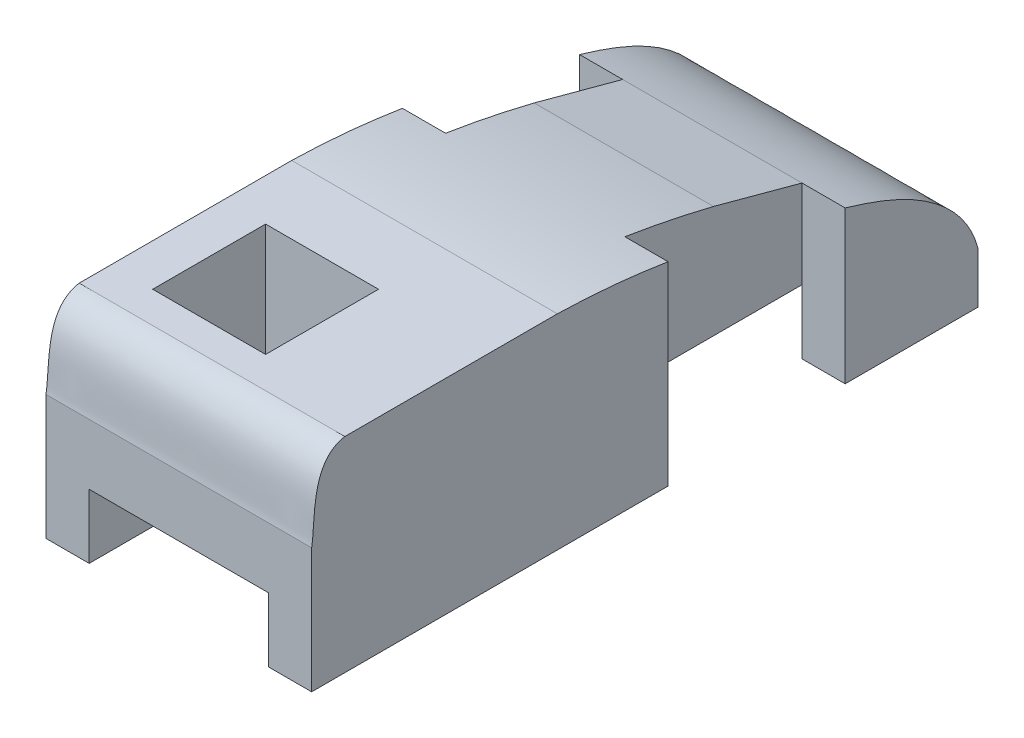
SolidWorks part; units mm, degrees
ref_plane "前视基准面" through (0, 0, 0) normal (0, 0, 1) x (1, 0, 0)
ref_plane "上视基准面" through (0, 0, 0) normal (0, 1, 0) x (1, 0, 0)
ref_plane "右视基准面" through (0, 0, 0) normal (1, 0, 0) x (0, 0, -1)
other "Configuration Table"
sketch "草图1" plane through (0, 0, 0) normal (0, 1, 0) x (1, 0, 0)
  line L1 (-50, 92.5) -> (50, 92.5)
  line L2 (-50, 92.5) -> (-50, -92.5)
  line L3 (-50, -92.5) -> (50, -92.5)
  line L4 (50, 92.5) -> (50, -92.5)
  line L5 (-50, 92.5) -> (50, -92.5) construction
  line L6 (-50, -92.5) -> (50, 92.5) construction
  point P0 (0, 0)
  dimension "D1" = 100
  dimension "D2" = 185
extrude "凸台-拉伸1" add sketch "草图1" along normal blind 100
sketch "草图2" plane through (0, 0, 92.5) normal (0, 0, 1) x (1, 0, 0)
  line L0 (-20.8417, 0) -> (-20.8417, 3.8) construction
  line L1 (-50, 0) -> (50, 0) construction
  line L2 (-20.8417, 3.8) -> (75.1632, 3.8) construction
  line L3 (75.1632, 3.8) -> (-71.0613, 3.8) construction
  line L4 (-50, 5.664) -> (-50, -9.7456) construction
  line L5 (-50, 100) -> (-50, 0) construction
  line L7 (50, 0) -> (-50, 0)
  line L8 (50, 0) -> (50, 3.8)
  line L9 (50, 3.8) -> (-50, 3.8)
  line L10 (-50, 0) -> (-50, 3.8)
  dimension "D1" = 3.8
extrude "切除-拉伸1" cut sketch "草图2" against normal offset from surface (155 mm away) 30 up to face at (0, 50, -92.5)
sketch "草图3" plane through (0, 0, 92.5) normal (0, 0, 1) x (1, 0, 0)
  line L0 (-20, 101.4471) -> (-20, -5.8655) construction
  line L1 (-4.3, 4.1859) -> (4.3, 4.1859) construction
  line L2 (-50, 3.8) -> (-20, 3.8) construction
  line L3 (-50, 3.8) -> (50, 3.8) construction
  line L4 (50, 3.8) -> (20, 3.8) construction
  line L5 (50, 3.8) -> (-50, 3.8) construction
  line L6 (20, 3.8) -> (20, 102.7774) construction
  line L7 (0, 0) -> (0, 12.6714) construction
  line L8 (-3.51, 3.8) -> (3.51, 3.8)
  line L9 (0, 3.8) -> (7.456, 3.8) construction
  line L10 (-9.3719, 10.6927) -> (9.3719, 10.6927) construction
  line L11 (-4.5, 11.5021) -> (4.5, 11.5021) construction
  line L12 (-9.3719, 10.6927) -> (-9.3719, 3.8) construction
  line L13 (-9.3719, 10.6927) -> (-4.3, 4.1859)
  line L14 (-4.3, 4.1859) -> (-4.3, 3.8) construction
  line L15 (8.9765, 11.5021) -> (8.9765, 10.6927) construction
  line L16 (9.3719, 10.6927) -> (4.3, 4.1859)
  line L17 (-4.5, 11.5021) -> (-8.9765, 11.5021)
  line L18 (4.5, 11.5021) -> (8.9765, 11.5021)
  line L19 (-8.9765, 11.5021) -> (-8.9765, 10.6927) construction
  line L21 (-4.5, 16.0021) -> (4.5, 16.0021) construction
  line L24 (-50, 100) -> (-50, 3.8) construction
  line L25 (-50, 16.0021) -> (-50, 3.8)
  line L26 (-50, 3.8) -> (-3.51, 3.8)
  line L28 (50, 100) -> (50, 3.8) construction
  line L29 (50, 16.0021) -> (50, 3.8)
  line L30 (50, 3.8) -> (3.51, 3.8)
  line L33 (20.5, 3.8) -> (3.51, 3.8)
  line L36 (-20.5, 3.8) -> (-3.51, 3.8)
  line L37 (0, 16.0021) -> (4, 16.0021)
  line L38 (0, 16.0021) -> (-4, 16.0021)
  line L39 (4, 16.0021) -> (4, 12.0021)
  line L40 (-4, 16.0021) -> (-4, 12.0021)
  line L41 (-4, 16.0021) -> (-20, 16.0021)
  line L42 (-20, 16.0021) -> (-20, 3.8)
  line L43 (-20, 3.8) -> (-3.51, 3.8)
  line L44 (4, 16.0021) -> (20, 16.0021)
  line L45 (20, 16.0021) -> (20, 3.8)
  line L46 (20, 3.8) -> (3.51, 3.8)
  arc A0 (-4.3, 4.1859) -> (-3.51, 3.8) centre (-3.51, 4.8016) ccw
  arc A1 (3.51, 3.8) -> (4.3, 4.1859) centre (3.51, 4.8016) ccw
  arc A2 (-9.3719, 10.6927) -> (-8.9765, 11.5021) centre (-8.3456, 10.6927) cw
  arc A3 (8.9765, 11.5021) -> (9.3719, 10.6927) centre (8.9765, 11.0008) cw
  arc A4 (-4, 12.0021) -> (-4.5, 11.5021) centre (-4.5, 12.0021) cw
  arc A5 (4, 12.0021) -> (4.5, 11.5021) centre (4.5, 12.0021) ccw
  point P21 (0, 3.8)
  point P24 (0, 10.6927)
  point P28 (0, 11.5021)
  point P29 (0, 4.1859)
  line M35 (-50, 3.8) -> (50, 3.8)
  dimension "D10" = 4.5
  dimension "D1" = 30
  dimension "D2" = 30
  dimension "D3" = 7.02
  dimension "D4" = 6.8927
  dimension "D5" = 8.25
  dimension "D6" = 8.6
  dimension "D7" = 4.4765
  dimension "D8" = 9
  dimension "D9" = 4.4765
  dimension "D11" = 4
  dimension "D12" = 4
  dimension "D13" = 4
extrude "切除-拉伸2" cut sketch "草图3" against normal offset from surface (155 mm away) 30 contours A4 L40 L41 L42 L36 A0 L13 A2 L17 | L39 A5 L18 A3 L16 A1 L45 L44 M35 up to face at (0, 50, -92.5)
sketch "草图4" plane through (0, 100, 0) normal (0, 1, 0) x (1, 0, 0)
  line L0 (50, -77.1603) -> (20.5, -77.1603) construction
  line L1 (50, -92.5) -> (50, 92.5) construction
  line L2 (20.5, -77.1603) -> (20.5, -102.6857) construction
  line L3 (20.5, -102.6857) -> (20.5, 96.3461) construction
  line L4 (57.5619, -92.5) -> (57.5619, -63) construction
  line L5 (-50, -92.5) -> (50, -92.5) construction
  line L6 (-68.401, -63) -> (56.5569, -63) construction
  line L8 (20.5, -63) -> (-5, -63)
  line L9 (20.5, -63) -> (20.5, -37.5)
  line L10 (20.5, -37.5) -> (-5, -37.5)
  line L11 (-5, -63) -> (-5, -37.5)
  dimension "D1" = 29.5
  dimension "D2" = 29.5
  dimension "D3" = 25.5
  dimension "D4" = 25.5
extrude "切除-拉伸3" cut sketch "草图4" against normal blind 79
sketch "草图6" plane through (0, 100, 0) normal (0, 1, 0) x (1, 0, 0)
  line L0 (-39.7063, 92.5) -> (-39.7063, 82.5)
  line L1 (50, 92.5) -> (-50, 92.5) construction
  line L2 (-39.7063, 82.5) -> (82.0818, 82.5)
  line L3 (-39.7063, 82.5) -> (-63.7302, 82.5)
  line M6 (50, -92.5) -> (50, 92.5)
  line M7 (50, 92.5) -> (-50, 92.5)
  line M8 (-50, 92.5) -> (-50, -92.5)
  dimension "D1" = 10
extrude "切除-拉伸4" cut sketch "草图6" against normal through all contours L0 L2 M6 M7 | L3 L0 M7 M8
sketch "草图7" plane through (-50, 0, 0) normal (-1, 0, 0) x (0, 0, 1)
  line L0 (-62.5, 3.8) -> (-82.5, 3.8)
  line L1 (-82.5, 0) -> (-82.5, 100) construction
  line M3 (-82.5, 100) -> (-82.5, 0)
  line M4 (-82.5, 0) -> (-62.5, 0)
  line M5 (-62.5, 0) -> (-62.5, 3.8)
extrude "切除-拉伸5" cut sketch "草图7" against normal through all and the other way through all contours L0 M5 M3 M4
sketch "草图9" plane through (0, 0, 92.5) normal (0, 0, 1) x (1, 0, 0)
  line L0 (-9.3719, 10.6927) -> (-9.3719, 13.2927)
  line L1 (-9.3719, 13.2927) -> (-4, 13.2927)
  line L2 (-4, 12.0021) -> (-4, 16.0021) construction
  line L3 (-9.3719, 10.6927) -> (9.3719, 10.6927)
  line L4 (9.3719, 10.6927) -> (9.3719, 13.2927)
  line L5 (9.3719, 13.2927) -> (4, 13.2927)
  line L6 (4, 16.0021) -> (4, 12.0021) construction
  line L7 (-4, 13.2927) -> (4, 13.2927)
  dimension "D1" = 2.6
extrude "凸台-拉伸4" add sketch "草图9" against normal blind 160
sketch "草图10" plane through (0, 0, 92.5) normal (0, 0, 1) x (1, 0, 0)
  line L0 (-20, 16.0021) -> (-20, 17.8021)
  line L1 (-20, 17.8021) -> (-4, 17.8021)
  line L2 (-4, 17.8021) -> (-4, 16.0021)
  line L4 (4, 16.0021) -> (4, 17.8021)
  line L5 (4, 17.8021) -> (19.9985, 17.8021)
  line L6 (19.9985, 17.8021) -> (20, 16.0021)
  line L7 (20, 16.0021) -> (4, 16.0021) construction
  line L8 (4, 16.0021) -> (20, 16.0021) construction
  line L9 (-20, 16.0021) -> (-4, 16.0021)
  line L10 (4, 16.0021) -> (20, 16.0021)
  dimension "D1" = 1.8
  dimension "D2" = 1.8
extrude "切除-拉伸6" cut sketch "草图10" against normal blind 155
sketch "草图13" plane through (0, 3.8, 0) normal (0, -1, 0) x (1, 0, 0)
  line L11 (-30, 92.5) -> (-30, -82.5)
  line L12 (50, -82.5) -> (-50, -82.5) construction
  line L13 (-30, -82.5) -> (-50, -82.5)
  line L14 (-50, 92.5) -> (-30, 92.5)
  line L16 (-50, 92.5) -> (-50, -82.5)
  line L17 (50, 92.5) -> (30, 92.5)
  line L18 (50, 92.5) -> (20, 92.5) construction
  line L19 (30, 92.5) -> (30, -82.5)
  line L20 (30, -82.5) -> (50, -82.5)
  line L21 (50, -82.5) -> (50, 92.5)
  dimension "D3" = 20
  dimension "D4" = 20
extrude "切除-拉伸7" cut sketch "草图13" against normal through all
sketch "草图14" plane through (30, 0, 0) normal (1, 0, 0) x (0, 0, -1)
  line L0 (-92.5, 100) -> (-92.5, 50)
  line L1 (-92.5, 100) -> (-92.5, 3.8) construction
  line L2 (-92.5, 50) -> (82.5, 50)
  line L3 (82.5, 100) -> (82.5, 3.8) construction
  line L4 (82.5, 50) -> (82.5, 100)
  line L5 (82.5, 100) -> (-92.5, 100)
  dimension "D1" = 50
extrude "切除-拉伸8" cut sketch "草图14" against normal through all
sketch "草图15" plane through (0, 3.8, 0) normal (0, -1, 0) x (1, 0, 0)
  line L0 (-30, -82.5) -> (-30, -72.5)
  line L1 (-30, -82.5) -> (-30, 92.5) construction
  line L2 (-30, -72.5) -> (30, -72.5)
  line L3 (30, 92.5) -> (30, -82.5) construction
  line L4 (30, -72.5) -> (30, -82.5)
  line L5 (30, -82.5) -> (-30, -82.5)
  dimension "D1" = 10
extrude "切除-拉伸9" cut sketch "草图15" against normal through all
sketch "草图16" plane through (0, 50, 0) normal (0, 1, 0) x (1, 0, 0)
  line L0 (30, -92.5) -> (30, 72.5) construction
  line L1 (-30, -92.5) -> (30, -92.5)
  line L2 (-30, -92.5) -> (-30, -78)
  line L3 (-30, -78) -> (30, -78)
  line L4 (30, -92.5) -> (30, -78)
  dimension "D1" = 14.5
extrude "切除-拉伸10" cut sketch "草图16" against normal through all
sketch "草图17" plane through (30, 0, 0) normal (1, 0, 0) x (0, 0, -1)
  line L0 (-78, 3.8) -> (72.5, 3.8) construction
  line L1 (-78, 50) -> (-63, 50) construction
  line L2 (-78, 50) -> (-78, 3.8) construction
  line L3 (-78, 3.8) -> (-63, 3.8) construction
  line L4 (-63, 50) -> (-63, 3.8) construction
  line L5 (72.5, 50) -> (72.5, 3.8) construction
  line L6 (-63, 50) -> (-37.5, 50)
  line L7 (-63, 50) -> (-63, 3.8)
  line L8 (-63, 3.8) -> (-37.5, 3.8)
  line L9 (-37.5, 50) -> (-37.5, 3.8)
  line L10 (-37.5, 50) -> (-22.5, 50)
  line L11 (-37.5, 50) -> (-37.5, 3.8)
  line L12 (-37.5, 3.8) -> (-22.5, 3.8)
  line L13 (-22.5, 50) -> (-22.5, 3.8)
  line L14 (72.5, 15.3113) -> (72.5, 3.8)
  line L15 (72.5, 3.8) -> (-22.5, 3.8)
  line L16 (-22.5, 50) -> (72.5, 50)
  line L17 (72.5, 50) -> (72.5, 15.3113)
  spline S0 degree 3 poles (-22.5, 50) (-9.3307, 49.7061) (11.0858, 46.8271) (38.2398, 39.499) (59.6886, 33.2729) (70.6797, 22.2955) (72.5, 15.3113) knots 0 0 0 0 0.374533 0.581855 0.802431 1 1 1 1
  line M3 (72.5, 50) -> (-78, 50)
  line M6 (72.5, 3.8) -> (72.5, 50)
  dimension "D1" = 15
  dimension "D2" = 25.5
  dimension "D3" = 15
extrude "切除-拉伸11" cut sketch "草图17" against normal through all contours S0 M3 M6
sketch "草图24" plane through (0, 0, 78) normal (0, 0, 1) x (1, 0, 0)
  line L0 (9.3719, 11.309) -> (9.3719, 10.6927)
  line L1 (9.3719, 10.6927) -> (4.3, 4.1859) construction
  arc A0 (9.3719, 10.6927) -> (9.3719, 11.309) centre (8.9765, 11.0008) ccw construction
  arc M6 (9.3719, 10.6927) -> (9.3719, 11.309) centre (8.9765, 11.0008) ccw
extrude "切除-拉伸21" cut sketch "草图24" against normal blind 140.5 and the other way through all contours L0 M6
sketch "草图28" plane through (30, 0, 0) normal (1, 0, 0) x (0, 0, -1)
  line L0 (-78, 3.8) -> (72.5, 3.8) construction
  line L1 (-78, 50) -> (-63, 50)
  line L2 (-78, 50) -> (-78, 3.8)
  line L3 (-78, 3.8) -> (-63, 3.8)
  line L4 (-63, 50) -> (-63, 3.8)
  spline S0 degree 3 poles (-70.5, 50) (-78.4109, 48.6564) (-77.0738, 36.8433) (-78, 31.9829) knots 0 0 0 0 1 1 1 1
  line M9 (-78, 50) -> (-78, 3.8)
  dimension "D1" = 15
extrude "切除-拉伸26" cut sketch "草图28" against normal through all contours S0 L1 M9
sketch "草图34" plane through (0, 3.8, 0) normal (0, -1, 0) x (1, 0, 0)
  line L0 (-30, -72.5) -> (-30, 78) construction
  line L1 (-20, -62.5) -> (-30, -62.5)
  line L2 (-20, -62.5) -> (-20, -42.5)
  line L3 (-20, -42.5) -> (-30, -42.5)
  line L4 (-30, -62.5) -> (-30, -42.5)
  line L5 (30, 78) -> (30, -72.5) construction
  line L6 (20, -62.5) -> (30, -62.5)
  line L7 (20, -62.5) -> (20, -42.5)
  line L8 (20, -42.5) -> (30, -42.5)
  line L9 (30, -62.5) -> (30, -42.5)
  line L10 (-9.3719, -62.5) -> (-9.3719, 78) construction
  line L11 (-9.3719, -42.5) -> (9.3719, -42.5)
  line L12 (-9.3719, -42.5) -> (-9.3719, -62.5)
  line L13 (-9.3719, -62.5) -> (9.3719, -62.5)
  line L14 (9.3719, -42.5) -> (9.3719, -62.5)
  line L15 (20, -62.5) -> (3.51, -62.5) construction
  line L16 (4.3, -62.5) -> (9.3719, -62.5) construction
  line L17 (20, -62.5) -> (20, 78) construction
  line L18 (-20, -42.5) -> (-30, -42.5)
  line L19 (-20, -42.5) -> (-20, -22.5)
  line L20 (-20, -22.5) -> (-30, -22.5)
  line L21 (-30, -42.5) -> (-30, -22.5)
  line L22 (-9.3719, -22.5) -> (9.3719, -22.5)
  line L23 (-9.3719, -22.5) -> (-9.3719, -42.5)
  line L24 (-9.3719, -42.5) -> (9.3719, -42.5)
  line L25 (9.3719, -22.5) -> (9.3719, -42.5)
  line L26 (20, -22.5) -> (30, -22.5)
  line L27 (20, -22.5) -> (20, -42.5)
  line L28 (20, -42.5) -> (30, -42.5)
  line L29 (30, -22.5) -> (30, -42.5)
  line L31 (-20, -22.5) -> (-30, -22.5)
  line L32 (-20, -22.5) -> (-20, -2.5)
  line L33 (-20, -2.5) -> (-30, -2.5)
  line L34 (-30, -22.5) -> (-30, -2.5)
  line L35 (-20, -2.5) -> (-30, -2.5)
  line L36 (-20, -2.5) -> (-20, 78)
  line L37 (-20, 78) -> (-30, 78)
  line L38 (-30, -2.5) -> (-30, 78)
  line L39 (-9.3719, 78) -> (9.3719, 78)
  line L40 (-9.3719, 78) -> (-9.3719, -2.5)
  line L41 (-9.3719, -2.5) -> (9.3719, -2.5)
  line L42 (9.3719, 78) -> (9.3719, -2.5)
  line L43 (20, 78) -> (30, 78)
  line L44 (20, 78) -> (20, -2.5)
  line L45 (20, -2.5) -> (30, -2.5)
  line L46 (30, 78) -> (30, -2.5)
  line M6 (30, -72.5) -> (30, 78)
  line M8 (20, 78) -> (20, -62.5)
  line M14 (-20, -62.5) -> (-20, 78)
  line M16 (-30, 78) -> (-30, -72.5)
  dimension "D1" = 20
  dimension "D2" = 20
  dimension "D3" = 20
  dimension "D4" = 20
  dimension "D5" = 20
extrude "切除-拉伸31" cut sketch "草图34" against normal through all contours L20 L3 M14 M16 | L26 L8 M8 M6
sketch "草图35" plane through (0, 3.8, 0) normal (0, -1, 0) x (1, 0, 0)
  line L0 (-30, -22.5) -> (-30, 78) construction
  line L1 (-20, -22.5) -> (-30, -22.5)
  line L2 (-20, -22.5) -> (-20, -2.5)
  line L3 (-20, -2.5) -> (-30, -2.5)
  line L4 (-30, -22.5) -> (-30, -2.5)
  line L5 (-9.3719, -62.5) -> (-9.3719, 78) construction
  line L6 (-9.3719, -2.5) -> (9.3719, -2.5)
  line L7 (-9.3719, -2.5) -> (-9.3719, -22.5)
  line L8 (-9.3719, -22.5) -> (9.3719, -22.5)
  line L9 (9.3719, -2.5) -> (9.3719, -22.5)
  line L10 (20, -22.5) -> (20, 78) construction
  line L11 (20, -2.5) -> (30, -2.5)
  line L12 (20, -2.5) -> (20, -22.5)
  line L13 (20, -22.5) -> (30, -22.5)
  line L14 (30, -2.5) -> (30, -22.5)
  line L15 (30, 78) -> (30, -22.5) construction
  line L17 (-9.3719, 78) -> (9.3719, 78)
  line L18 (-9.3719, 78) -> (-9.3719, -2.5)
  line L19 (-9.3719, -2.5) -> (9.3719, -2.5)
  line L20 (9.3719, 78) -> (9.3719, -2.5)
  dimension "D1" = 20
extrude "切除-拉伸32" cut sketch "草图35" against normal blind 14 contours L20 L17 L18 L6
sketch "草图40" plane through (0, 0, -2.5) normal (0, 0, 1) x (1, 0, 0)
  line L0 (9.3719, 13.2927) -> (4, 13.2927) construction
  line L1 (4, 17.8021) -> (3.75, 17.8021)
  line L2 (4, 17.8021) -> (4, 13.2927)
  line L3 (4, 13.2927) -> (3.75, 13.2927)
  line L4 (3.75, 17.8021) -> (3.75, 13.2927)
  line L5 (-4, 17.8) -> (4, 17.8) construction
  line L6 (-4, 13.2927) -> (-3.75, 13.2927)
  line L7 (-4, 13.2927) -> (-4, 17.8)
  line L8 (-4, 17.8) -> (-3.75, 17.8)
  line L9 (-3.75, 13.2927) -> (-3.75, 17.8)
  line L10 (9.3719, 10.6927) -> (9.3719, 13.2927) construction
  line L11 (-9.3719, 13.2927) -> (9.3719, 13.2927)
  line L12 (-9.3719, 13.2927) -> (-9.3719, 12.7927)
  line L13 (-9.3719, 12.7927) -> (9.3719, 12.7927)
  line L14 (9.3719, 13.2927) -> (9.3719, 12.7927)
  line L16 (-3.75, 13.2927) -> (3.75, 13.2927)
  line L17 (-3.75, 13.2927) -> (-3.75, 12.7927)
  line L18 (-3.75, 12.7927) -> (3.75, 12.7927)
  line L19 (3.75, 13.2927) -> (3.75, 12.7927)
  line M7 (9.3719, 10.6927) -> (9.3719, 13.2927)
  line M8 (9.3719, 13.2927) -> (4, 13.2927)
  line M9 (4, 13.2927) -> (4, 17.8)
  line M10 (4, 17.8) -> (-4, 17.8)
  line M12 (-4, 13.2927) -> (-9.3719, 13.2927)
  line M13 (-9.3719, 13.2927) -> (-9.3719, 10.6927)
  dimension "D1" = 0.25
  dimension "D2" = 0.25
  dimension "D3" = 0.5
extrude "切除-拉伸35" cut sketch "草图40" against normal blind 60 contours L4 L3 M10 M9 | L3 L19 L13 M7 M8 | L17 L6 L13 M12 M13
sketch "草图41" plane through (0, 0, 78) normal (0, 0, 1) x (1, 0, 0)
  line L0 (-20, 3.8) -> (-30, 3.8) construction
  line L1 (-20, 17.8021) -> (19.9985, 17.8021)
  line L3 (-20, 18.3021) -> (19.9985, 18.3021)
  line L5 (-3.75, 17.8) -> (3.75, 17.8)
  line L6 (-3.75, 17.8) -> (-3.75, 18.3021)
  line L8 (3.75, 17.8) -> (3.75, 18.3021)
  line L11 (-20, 17.8) -> (-3.75, 17.8)
  line L17 (-20, 18.3021) -> (-20.25, 18.3021)
  line L18 (-20, 18.3021) -> (-20, 3.8)
  line L19 (-20, 3.8) -> (-20.25, 3.8)
  line L20 (-20.25, 18.3021) -> (-20.25, 3.8)
  line L21 (30, 3.8) -> (20, 3.8) construction
  line L22 (19.9985, 18.3021) -> (20.2485, 18.3021)
  line L23 (19.9985, 18.3021) -> (19.9985, 3.8)
  line L24 (19.9985, 3.8) -> (20.2485, 3.8)
  line L25 (20.2485, 18.3021) -> (20.2485, 3.8)
  dimension "D1" = 0.5
  dimension "D2" = 0.25
  dimension "D3" = 0.25
extrude "切除-拉伸36" cut sketch "草图41" against normal blind 140.5
sketch "草图43" plane through (0, 0, 78) normal (0, 0, 1) x (1, 0, 0)
  line L0 (-4, 17.8) -> (4, 17.8) construction
  line L1 (-4, 17.8021) -> (-3.75, 17.8021)
  line L2 (-4, 17.8021) -> (-4, 17.8)
  line L3 (-4, 17.8) -> (-3.75, 17.8)
  line L4 (-3.75, 17.8021) -> (-3.75, 17.8)
  line L5 (-4, 17.8) -> (-3.75, 17.8) construction
  line L7 (3.75, 17.8021) -> (4, 17.8021)
  line L8 (3.75, 17.8021) -> (3.75, 17.8)
  line L9 (3.75, 17.8) -> (4, 17.8)
  line L10 (4, 17.8021) -> (4, 17.8)
extrude "切除-拉伸37" cut sketch "草图43" against normal blind 140.5
sketch "草图44" plane through (0, 0, 78) normal (0, 0, 1) x (1, 0, 0)
  line L1 (-3.75, 18.3021) -> (3.75, 18.3021)
  line L2 (-3.75, 18.3021) -> (-3.75, 17.8)
  line L3 (-3.75, 17.8) -> (3.75, 17.8)
  line L4 (3.75, 18.3021) -> (3.75, 17.8)
extrude "切除-拉伸38" cut sketch "草图44" against normal offset from surface (80.4999 mm away) 0.0001 up to face at (0, 10.3288, -2.5)
sketch "草图45" plane through (0, 3.8, 0) normal (0, -1, 0) x (1, 0, 0)
  line L0 (-30, -22.5) -> (-30, 78) construction
  line L1 (-30, -2.5) -> (-20.25, -2.5)
  line L2 (-30, -2.5) -> (-30, -22.5)
  line L3 (-30, -22.5) -> (-20.25, -22.5)
  line L4 (-20.25, -2.5) -> (-20.25, -22.5)
  line L5 (-9.3719, -2.5) -> (-4.3, -2.5) construction
  line L6 (20.2485, -22.5) -> (20.2485, 78) construction
  line L7 (20.2485, -2.5) -> (30, -2.5)
  line L8 (20.2485, -2.5) -> (20.2485, -22.5)
  line L9 (20.2485, -22.5) -> (30, -22.5)
  line L10 (30, -2.5) -> (30, -22.5)
extrude "切除-拉伸39" cut sketch "草图45" against normal through all
sketch "草图46" plane through (0, 18.3021, 0) normal (0, -1, 0) x (1, 0, 0)
  line L1 (20, -22.5) -> (20.2485, -22.5)
  line L2 (20, -22.5) -> (20, -42.5)
  line L3 (20, -42.5) -> (20.2485, -42.5)
  line L4 (20.2485, -22.5) -> (20.2485, -42.5)
  line L5 (-20, -22.5) -> (-20.25, -22.5)
  line L6 (-20, -22.5) -> (-20, -42.5)
  line L7 (-20, -42.5) -> (-20.25, -42.5)
  line L8 (-20.25, -22.5) -> (-20.25, -42.5)
extrude "凸台-拉伸5" add sketch "草图46" against normal through all
sketch "草图47" plane through (-20.25, 0, 0) normal (-1, 0, 0) x (0, 0, 1)
  spline S0 degree 1 poles (-42.5, 38.204) (-22.5, 43.618) knots 0 0 1 1
  line M3 (-22.5, 43.618) -> (-22.5, 50)
  line M4 (-22.5, 50) -> (-42.5, 50)
  line M5 (-42.5, 50) -> (-42.5, 38.204)
extrude "切除-拉伸40" cut sketch "草图47" against normal through all and the other way through all contours S0 M5 M3 M4
sketch "草图54" plane through (0, 50, 0) normal (0, 1, 0) x (1, 0, 0)
  line L1 (20.5, -37.5) -> (-5, -37.5)
  line L2 (20.5, -37.5) -> (20.5, -37)
  line L3 (20.5, -37) -> (-5, -37)
  line L4 (-5, -37.5) -> (-5, -37)
  line L5 (-5, -37) -> (-5.5, -37)
  line L6 (-5, -37) -> (-5, -63)
  line L7 (-5, -63) -> (-5.5, -63)
  line L8 (-5.5, -37) -> (-5.5, -63)
  dimension "D1" = 0.5
  dimension "D2" = 0.5
extrude "切除-拉伸41" cut sketch "草图54" against normal blind 29 contours L4 L1 L2 L3 | L5 L8 L7 L6
sketch "草图55" plane through (0, 50, 0) normal (0, 1, 0) x (1, 0, 0)
  line L1 (-5.5, -37) -> (20.5, -37)
  line L2 (-5.5, -37) -> (-5.5, -63)
  line L3 (-5.5, -63) -> (20.5, -63)
  line L4 (20.5, -37) -> (20.5, -63)
extrude "凸台-拉伸6" add sketch "草图55" against normal blind 29
sketch "草图56" plane through (0, 50, 0) normal (0, 1, 0) x (1, 0, 0)
  line L0 (-30, -70.5) -> (-30, -22.5) construction
  line L1 (-20.5, -37.9) -> (5, -37.9)
  line L2 (-20.5, -37.9) -> (-20.5, -63.4)
  line L3 (-20.5, -63.4) -> (5, -63.4)
  line L4 (5, -37.9) -> (5, -63.4)
  line L5 (-20.5, -63.4) -> (-30, -63.4) construction
  line L7 (-20.5, -37.9) -> (-30, -37.9) construction
  line L8 (-30, -63.4) -> (-30, -37.9) construction
  line L9 (-5.3967, -63.4) -> (-5.3967, -78) construction
  line L10 (-30, -78) -> (30, -78) construction
  dimension "D1" = 9.5
  dimension "D2" = 14.6
  dimension "D3" = 25.5
  dimension "D4" = 25.5
extrude "切除-拉伸42" cut sketch "草图56" against normal blind 29
